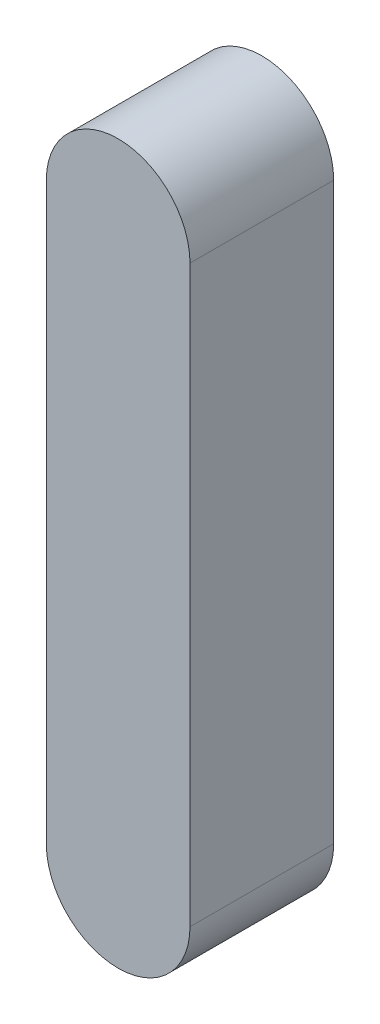
SolidWorks part; units mm, degrees
ref_plane "Front Plane" through (0, 0, 0) normal (0, 0, 1) x (1, 0, 0)
ref_plane "Top Plane" through (0, 0, 0) normal (0, 1, 0) x (1, 0, 0)
ref_plane "Right Plane" through (0, 0, 0) normal (1, 0, 0) x (0, 0, -1)
sketch "Sketch1" plane through (0, 0, 0) normal (0, 0, 1) x (1, 0, 0)
  line L0 (1, -148) -> (1, -140) construction
  line L1 (-1, -140) -> (-1, -148) construction
  line L2 (1, -148) -> (1, -140)
  line L3 (-1, -140) -> (-1, -148)
  arc A0 (1, -140) -> (-1, -140) centre (0, -140) ccw construction
  arc A1 (-1, -148) -> (1, -148) centre (0, -148) ccw construction
  arc A2 (1, -140) -> (-1, -140) centre (0, -140) ccw
  arc A3 (-1, -148) -> (1, -148) centre (0, -148) ccw
extrude "Boss-Extrude1" add sketch "Sketch1" along normal blind 2
